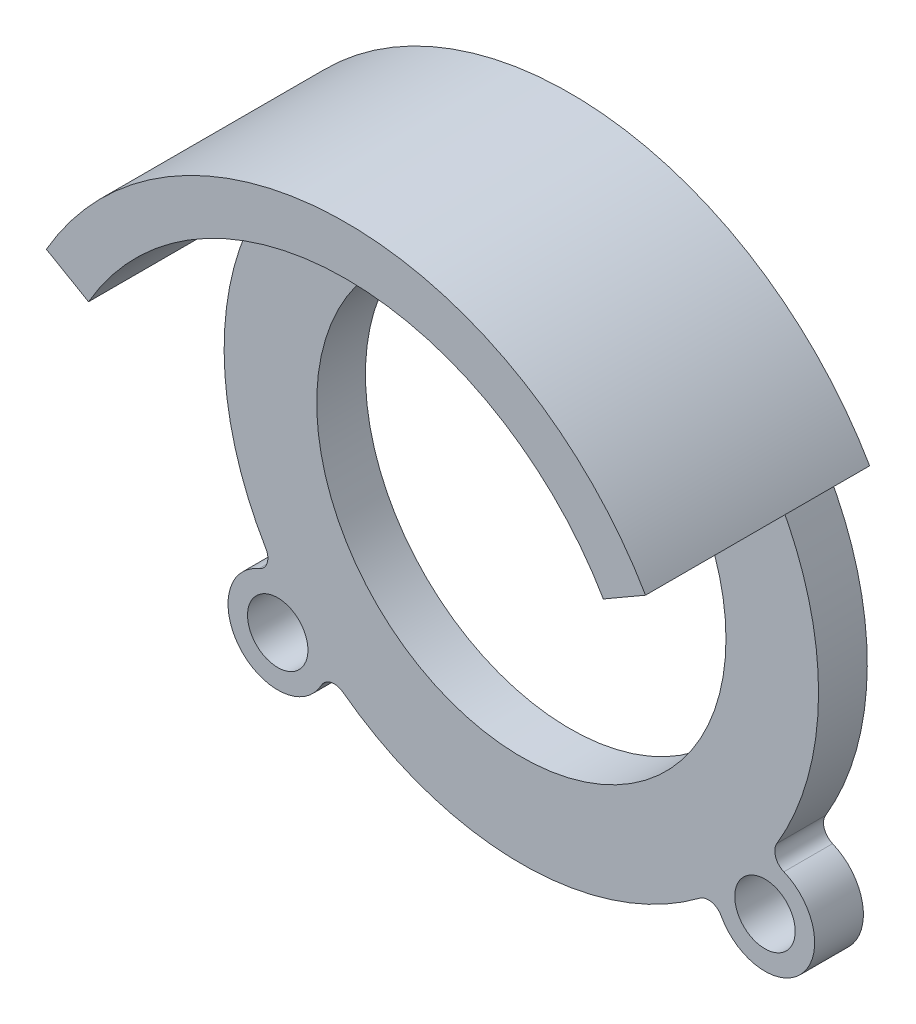
SolidWorks part; units mm, degrees
ref_plane "Plano frontal" through (0, 0, 0) normal (0, 0, 1) x (1, 0, 0)
ref_plane "Plano superior" through (0, 0, 0) normal (0, 1, 0) x (1, 0, 0)
ref_plane "Plano direito" through (0, 0, 0) normal (1, 0, 0) x (0, 0, -1)
sketch "Esboço1" plane through (0, 0, 0) normal (0, 0, 1) x (1, 0, 0)
  line L0 (0, 0) -> (-25, -22.4491) construction
  line L1 (0, 0) -> (25, -22.4491) construction
  line L2 (25, -22.4491) -> (-25, -22.4491) construction
  line L3 (0, 0) -> (0, -22.4491) construction
  line L4 (-26.4138, 15.25) -> (-30.7439, 17.75)
  line L5 (26.4138, 15.25) -> (30.7439, 17.75)
  line L6 (0, 35.5) -> (0, 0) construction
  line L7 (-26.4138, 15.25) -> (0, 0) construction
  line L8 (0, 0) -> (26.4138, 15.25) construction
  arc A0 (26.2211, -15.579) -> (26.4138, 15.25) centre (0, 0) ccw
  circle A1 centre (0, 0) radius 21
  circle A2 centre (25, -22.4491) radius 3.1
  circle A3 centre (-25, -22.4491) radius 3.1
  arc A5 (26.2211, -15.579) -> (26.94, -17.7325) centre (27.5106, -16.3452) ccw
  arc A6 (-26.94, -17.7325) -> (-20.5186, -24.8836) centre (-25, -22.4491) ccw
  arc A7 (-26.94, -17.7325) -> (-26.2211, -15.579) centre (-27.5106, -16.3452) ccw
  arc A8 (-18.3005, -24.3996) -> (-20.5186, -24.8836) centre (-19.2005, -25.5996) ccw
  arc A9 (20.5186, -24.8836) -> (18.3005, -24.3996) centre (19.2005, -25.5996) ccw
  arc A10 (20.5186, -24.8836) -> (26.94, -17.7325) centre (25, -22.4491) ccw
  arc A11 (-18.3005, -24.3996) -> (18.3005, -24.3996) centre (0, 0) ccw
  arc A12 (-30.7439, 17.75) -> (30.7439, 17.75) centre (0, 0) cw
  arc A13 (-26.4138, 15.25) -> (-26.2211, -15.579) centre (0, 0) ccw
  dimension "D1" = 61
  dimension "D2" = 42
  dimension "D4" = 6.2
  dimension "D5" = 3
  dimension "D6" = 2
  dimension "D7" = 2
  dimension "D9" = 14.5
  dimension "D3" = 50
  dimension "D8" = 120
extrude "Ressalto-extrusão1" add sketch "Esboço1" along normal blind 5
sketch "Esboço2" plane through (0, 0, 5) normal (0, 0, 1) x (1, 0, 0)
  line L0 (-26.4138, 15.25) -> (-30.7439, 17.75)
  line L1 (26.4138, 15.25) -> (30.7439, 17.75)
  line L2 (-26.4138, 15.25) -> (0, 0) construction
  line L3 (0, 0) -> (26.4138, 15.25) construction
  line L4 (0, 0) -> (0, 35.5) construction
  arc A0 (-26.4138, 15.25) -> (26.4138, 15.25) centre (0, 0) cw
  arc A1 (26.2211, -15.579) -> (26.4138, 15.25) centre (0, 0) ccw construction
  arc A2 (-30.7439, 17.75) -> (30.7439, 17.75) centre (0, 0) cw
  dimension "D2" = 120
  dimension "D1" = 5
extrude "Ressalto-extrusão2" add sketch "Esboço2" along normal blind 18
